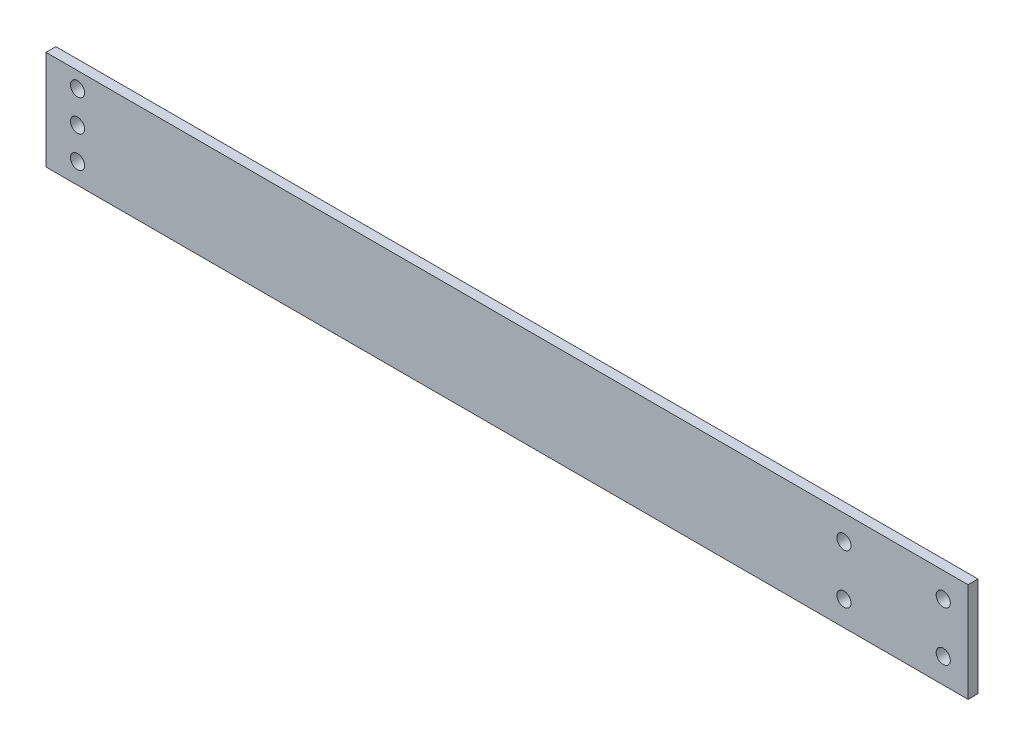
SolidWorks part; units mm, degrees
ref_plane "Front Plane" through (0, 0, 0) normal (0, 0, 1) x (1, 0, 0)
ref_plane "Top Plane" through (0, 0, 0) normal (0, 1, 0) x (1, 0, 0)
ref_plane "Right Plane" through (0, 0, 0) normal (1, 0, 0) x (0, 0, -1)
sketch "Sketch1" plane through (0, 0, 0) normal (0, 0, 1) x (1, 0, 0)
  line L1 (-92.855, -10) -> (92.855, -10)
  line L2 (-92.855, -10) -> (-92.855, 10)
  line L3 (-92.855, 10) -> (92.855, 10)
  line L4 (92.855, -10) -> (92.855, 10)
  line L5 (-92.855, -10) -> (92.855, 10) construction
  line L6 (-92.855, 10) -> (92.855, -10) construction
  point P0 (0, 0)
  dimension "D1" = 185.71
  dimension "D2" = 20
extrude "Boss-Extrude1" add sketch "Sketch1" along normal blind 2
sketch "Sketch2" plane through (0, 0, 2) normal (0, 0, 1) x (1, 0, 0)
  line L0 (92.855, 10) -> (-92.855, 10) construction
  line L1 (-92.855, 10) -> (-92.855, -10) construction
  line L2 (-86.505, 6.825) -> (-86.505, 0.475) construction
  line L3 (92.855, -10) -> (92.855, 10) construction
  line L4 (87.855, 5) -> (67.855, 5) construction
  circle A0 centre (-86.505, 6.825) radius 1.4224
  circle A2 centre (-86.505, 0.475) radius 1.4224
  circle A3 centre (-86.505, -5.875) radius 1.4224
  circle A4 centre (87.855, 5) radius 1.4224
  circle A5 centre (67.855, 5) radius 1.4224
  circle A6 centre (67.855, -5) radius 1.4224
  circle A7 centre (87.855, -5) radius 1.4224
  dimension "D1" = 2.8448
  dimension "D6" = 2.8448
  dimension "D2" = 3.175
  dimension "D3" = 6.35
  dimension "D5" = 6.35
  dimension "D7" = 5
  dimension "D8" = 5
  dimension "D11" = 20
  dimension "D4" = 3
  dimension "D9" = 2
  dimension "D10" = 2
extrude "Cut-Extrude1" cut sketch "Sketch2" against normal up to next
